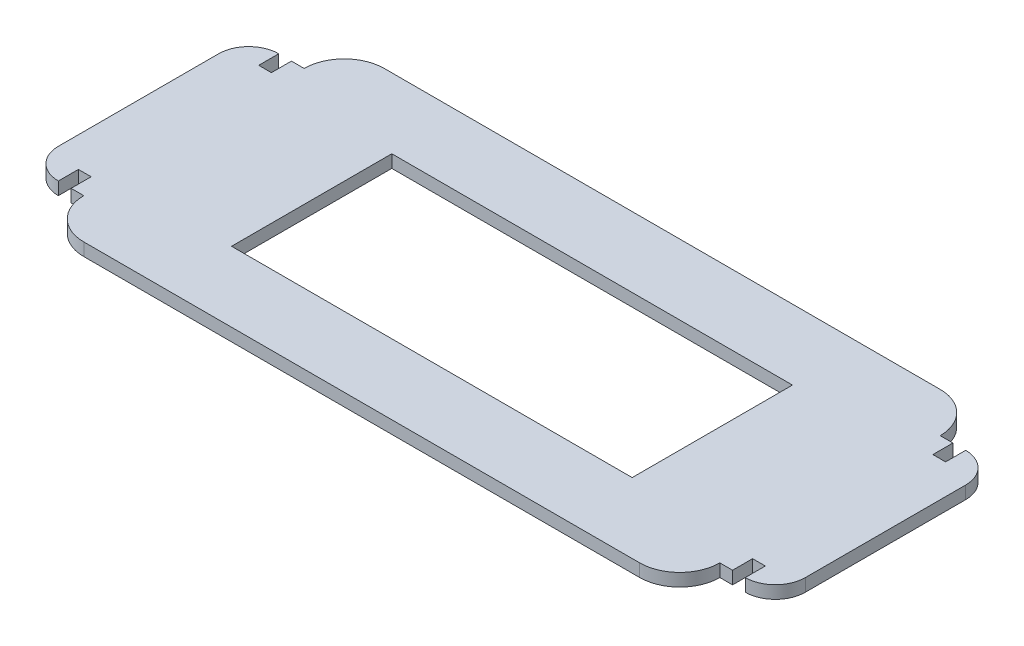
SolidWorks part; units mm, degrees
ref_plane "Front Plane" through (0, 0, 0) normal (0, 0, 1) x (1, 0, 0)
ref_plane "Top Plane" through (0, 0, 0) normal (0, 1, 0) x (1, 0, 0)
ref_plane "Right Plane" through (0, 0, 0) normal (1, 0, 0) x (0, 0, -1)
sketch "Sketch1" plane through (0, 0, 0) normal (0, 1, 0) x (1, 0, 0)
  line L1 (-69.375, 37.5) -> (69.375, 37.5)
  line L3 (-69.375, -37.5) -> (69.375, -37.5)
  line L5 (-50, 20) -> (50, 20)
  line L6 (50, 20) -> (50, -20)
  line L7 (50, -20) -> (-50, -20)
  line L8 (79.375, 27.5) -> (82.55, 27.5)
  line L9 (82.55, 27.5) -> (82.55, 22.5)
  line L10 (82.55, 22.5) -> (85.725, 22.5)
  line L11 (85.725, 22.5) -> (85.725, 27.5)
  line L12 (-50, -20) -> (-50, 20)
  line L13 (85.725, -22.5) -> (85.725, -27.5)
  line L14 (82.55, -22.5) -> (85.725, -22.5)
  line L15 (82.55, -27.5) -> (82.55, -22.5)
  line L16 (79.375, -27.5) -> (82.55, -27.5)
  line L17 (93.225, -20) -> (93.225, 20)
  line L19 (-79.375, 27.5) -> (-82.55, 27.5)
  line L20 (-82.55, 27.5) -> (-82.55, 22.5)
  line L21 (-82.55, 22.5) -> (-85.725, 22.5)
  line L22 (-85.725, 22.5) -> (-85.725, 27.5)
  line L23 (-93.225, -20) -> (-93.225, 20)
  line L24 (-85.725, -22.5) -> (-85.725, -27.5)
  line L25 (-82.55, -22.5) -> (-85.725, -22.5)
  line L26 (-82.55, -27.5) -> (-82.55, -22.5)
  line L27 (-79.375, -27.5) -> (-82.55, -27.5)
  arc A0 (79.375, 27.5) -> (69.375, 37.5) centre (69.375, 27.5) ccw
  arc A1 (79.375, -27.5) -> (69.375, -37.5) centre (69.375, -27.5) cw
  arc A2 (85.725, 27.5) -> (93.225, 20) centre (85.725, 20) cw
  arc A3 (85.725, -27.5) -> (93.225, -20) centre (85.725, -20) ccw
  arc A4 (-85.725, 27.5) -> (-93.225, 20) centre (-85.725, 20) ccw
  arc A5 (-85.725, -27.5) -> (-93.225, -20) centre (-85.725, -20) cw
  arc A6 (-79.375, -27.5) -> (-69.375, -37.5) centre (-69.375, -27.5) ccw
  arc A7 (-79.375, 27.5) -> (-69.375, 37.5) centre (-69.375, 27.5) cw
  point P0 (0, 0)
  point P4 (0, 0)
  point P27 (0, 20)
  dimension "D2" = 100
extrude "Boss-Extrude2" add sketch "Sketch1" along normal blind 3.175 contours L11 A2 L17 A3 L13 L14 L15 L16 A1 L3 A6 L27 L26 L25 L24 A5 L23 A4 L22 L21 L20 L19 A7 L1 A0 L8 L9 L10 | L12 L5 L6 L7
